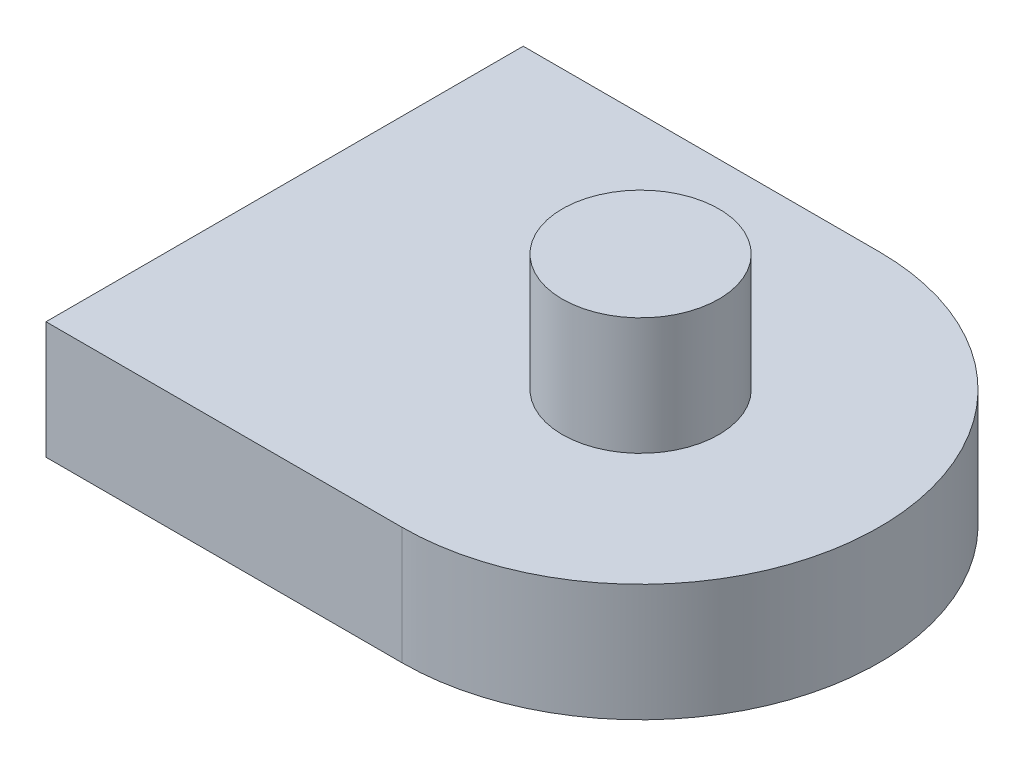
SolidWorks part; units mm, degrees
ref_plane "Front Plane" through (0, 0, 0) normal (0, 0, 1) x (1, 0, 0)
ref_plane "Top Plane" through (0, 0, 0) normal (0, 1, 0) x (1, 0, 0)
ref_plane "Right Plane" through (0, 0, 0) normal (1, 0, 0) x (0, 0, -1)
sketch "Sketch3" plane through (0, 0, 0) normal (0, 1, 0) x (1, 0, 0)
  line L1 (-20.3368, 8.2939) -> (-11.2368, 8.2939)
  line L2 (-20.3368, -3.9061) -> (-11.2368, -3.9061)
  line L3 (-20.3368, 8.2939) -> (-20.3368, -3.9061)
  arc A1 (-11.2368, -3.9061) -> (-11.2368, 8.2939) centre (-11.2368, 2.1939) ccw
  point P2 (-22.6342, 2.1939)
  point P7 (-20.3368, 8.2939)
  point P8 (-20.3368, -3.9061)
  dimension "D1" = 6.1
  dimension "D2" = 9.1
  dimension "D3" = 9.1
extrude "Boss-Extrude1" add sketch "Sketch3" along normal blind 3
sketch "Sketch4" plane through (0, 3, 0) normal (0, 1, 0) x (1, 0, 0)
  circle A0 centre (-11.2368, 2.1939) radius 2
  dimension "D1" = 4
extrude "Boss-Extrude2" add sketch "Sketch4" along normal blind 3 contours A0
